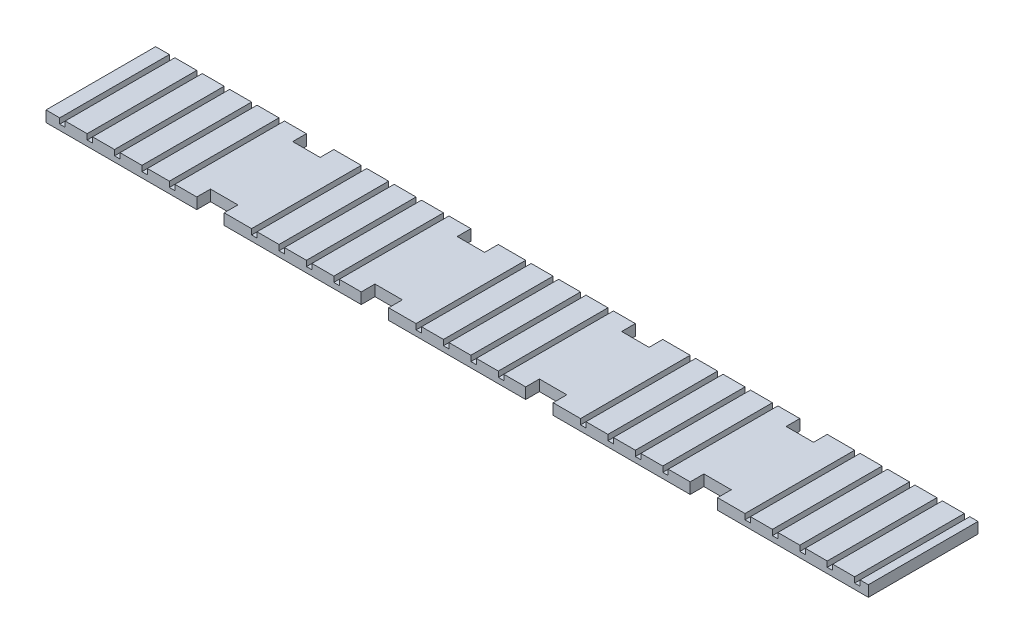
SolidWorks part; units mm, degrees
ref_plane "Front Plane" through (0, 0, 0) normal (0, 0, 1) x (1, 0, 0)
ref_plane "Top Plane" through (0, 0, 0) normal (0, 1, 0) x (1, 0, 0)
ref_plane "Right Plane" through (0, 0, 0) normal (1, 0, 0) x (0, 0, -1)
sketch "Sketch1" plane through (0, 0, 0) normal (0, 1, 0) x (1, 0, 0)
  line L0 (0, 20) -> (30, 20) construction
  line L1 (0, 0) -> (27.5, 0)
  line L2 (0, 0) -> (0, 20)
  line L3 (0, 20) -> (27.5, 20)
  line L4 (150, 0) -> (150, 20)
  line L5 (30, 20) -> (60, 20) construction
  line L6 (60, 20) -> (90, 20) construction
  line L7 (90, 20) -> (90.2101, 20) construction
  line L8 (90.2101, 20) -> (120, 20) construction
  line L10 (32.5, 20) -> (32.5, 17.5)
  line L11 (27.5, 20) -> (27.5, 17.5)
  line L12 (32.5, 17.5) -> (27.5, 17.5)
  line L13 (30, 20) -> (27.5, 17.5) construction
  line L14 (30, 20) -> (32.5, 17.5) construction
  line L15 (62.5, 20) -> (87.5, 20)
  line L16 (57.5, 20) -> (57.5, 17.5)
  line L17 (57.5, 17.5) -> (62.5, 17.5)
  line L18 (62.5, 17.5) -> (62.5, 20)
  line L20 (87.5, 20) -> (87.5, 17.5)
  line L21 (87.5, 17.5) -> (92.5, 17.5)
  line L22 (92.5, 17.5) -> (92.5, 20)
  line L23 (122.5, 20) -> (150, 20)
  line L24 (117.5, 20) -> (117.5, 17.5)
  line L25 (117.5, 17.5) -> (122.5, 17.5)
  line L26 (122.5, 17.5) -> (122.5, 20)
  line L27 (32.5, 20) -> (57.5, 20)
  line L28 (90, 20) -> (90.2101, 20)
  line L29 (92.5, 20) -> (117.5, 20)
  line L30 (27.5, 0) -> (27.5, 2.5)
  line L31 (27.5, 2.5) -> (32.5, 2.5)
  line L32 (32.5, 2.5) -> (32.5, 0)
  line L33 (57.5, 0) -> (57.5, 2.5)
  line L34 (57.5, 2.5) -> (62.5, 2.5)
  line L35 (62.5, 2.5) -> (62.5, 0)
  line L36 (87.5, 0) -> (87.5, 2.5)
  line L37 (87.5, 2.5) -> (92.5, 2.5)
  line L38 (92.5, 2.5) -> (92.5, 0)
  line L39 (117.5, 0) -> (117.5, 2.5)
  line L40 (117.5, 2.5) -> (122.5, 2.5)
  line L41 (122.5, 2.5) -> (122.5, 0)
  line L42 (32.5, 0) -> (57.5, 0)
  line L43 (62.5, 0) -> (87.5, 0)
  line L44 (92.5, 0) -> (117.5, 0)
  line L45 (122.5, 0) -> (150, 0)
  dimension "D1" = 27.5
  dimension "D2" = 32.5
  dimension "D3" = 57.5
  dimension "D4" = 17.5
  dimension "D7" = 90.2101
extrude "Boss-Extrude1" add sketch "Sketch1" along normal blind 2 contours L41 L45 L4 L23 L26 L25 L24 L29 L22 L21 L20 L15 L18 L17 L16 L27 L10 L12 L11 L3 L2 L1 L30 L31 L32 L42 L33 L34 L35 L43 L36 L37 L38 L44 L39 L40
sketch "Sketch2" plane through (0, 2, 0) normal (0, 1, 0) x (1, 0, 0)
  line L0 (0, 0) -> (27.5, 0) construction
  line L1 (2.5, 0) -> (3.5, 0)
  line L2 (2.5, 0) -> (2.5, 20)
  line L3 (2.5, 20) -> (3.5, 20)
  line L4 (3.5, 0) -> (3.5, 20)
  line L5 (0, 20) -> (27.5, 20) construction
  line L6 (0, 0) -> (0, 20) construction
  line L7 (7.5, 0) -> (7.5, 20)
  line L8 (7.5, 0) -> (8.5, 0)
  line L9 (8.5, 0) -> (8.5, 20)
  line L10 (7.5, 20) -> (8.5, 20)
  line L11 (12.5, 0) -> (12.5, 20)
  line L12 (12.5, 0) -> (13.5, 0)
  line L13 (13.5, 0) -> (13.5, 20)
  line L14 (12.5, 20) -> (13.5, 20)
  line L15 (17.5, 0) -> (17.5, 20)
  line L16 (17.5, 0) -> (18.5, 0)
  line L17 (18.5, 0) -> (18.5, 20)
  line L18 (17.5, 20) -> (18.5, 20)
  line L19 (22.5, 0) -> (22.5, 20)
  line L20 (22.5, 0) -> (23.5, 0)
  line L21 (23.5, 0) -> (23.5, 20)
  line L22 (22.5, 20) -> (23.5, 20)
  line L23 (27.5, 0) -> (27.5, 20) [skipped]
  line L24 (27.5, 0) -> (28.5, 0) [skipped]
  line L25 (28.5, 0) -> (28.5, 20) [skipped]
  line L26 (27.5, 20) -> (28.5, 20) [skipped]
  line L27 (32.5, 0) -> (32.5, 20) [skipped]
  line L28 (32.5, 0) -> (33.5, 0) [skipped]
  line L29 (33.5, 0) -> (33.5, 20) [skipped]
  line L30 (32.5, 20) -> (33.5, 20) [skipped]
  line L31 (37.5, 0) -> (37.5, 20)
  line L32 (37.5, 0) -> (38.5, 0)
  line L33 (38.5, 0) -> (38.5, 20)
  line L34 (37.5, 20) -> (38.5, 20)
  line L35 (42.5, 0) -> (42.5, 20)
  line L36 (42.5, 0) -> (43.5, 0)
  line L37 (43.5, 0) -> (43.5, 20)
  line L38 (42.5, 20) -> (43.5, 20)
  line L39 (47.5, 0) -> (47.5, 20)
  line L40 (47.5, 0) -> (48.5, 0)
  line L41 (48.5, 0) -> (48.5, 20)
  line L42 (47.5, 20) -> (48.5, 20)
  line L43 (52.5, 0) -> (52.5, 20)
  line L44 (52.5, 0) -> (53.5, 0)
  line L45 (53.5, 0) -> (53.5, 20)
  line L46 (52.5, 20) -> (53.5, 20)
  line L47 (57.5, 0) -> (57.5, 20) [skipped]
  line L48 (57.5, 0) -> (58.5, 0) [skipped]
  line L49 (58.5, 0) -> (58.5, 20) [skipped]
  line L50 (57.5, 20) -> (58.5, 20) [skipped]
  line L51 (62.5, 0) -> (62.5, 20) [skipped]
  line L52 (62.5, 0) -> (63.5, 0) [skipped]
  line L53 (63.5, 0) -> (63.5, 20) [skipped]
  line L54 (62.5, 20) -> (63.5, 20) [skipped]
  line L55 (67.5, 0) -> (67.5, 20)
  line L56 (67.5, 0) -> (68.5, 0)
  line L57 (68.5, 0) -> (68.5, 20)
  line L58 (67.5, 20) -> (68.5, 20)
  line L59 (72.5, 0) -> (72.5, 20)
  line L60 (72.5, 0) -> (73.5, 0)
  line L61 (73.5, 0) -> (73.5, 20)
  line L62 (72.5, 20) -> (73.5, 20)
  line L63 (77.5, 0) -> (77.5, 20)
  line L64 (77.5, 0) -> (78.5, 0)
  line L65 (78.5, 0) -> (78.5, 20)
  line L66 (77.5, 20) -> (78.5, 20)
  line L67 (82.5, 0) -> (82.5, 20)
  line L68 (82.5, 0) -> (83.5, 0)
  line L69 (83.5, 0) -> (83.5, 20)
  line L70 (82.5, 20) -> (83.5, 20)
  line L71 (87.5, 0) -> (87.5, 20) [skipped]
  line L72 (87.5, 0) -> (88.5, 0) [skipped]
  line L73 (88.5, 0) -> (88.5, 20) [skipped]
  line L74 (87.5, 20) -> (88.5, 20) [skipped]
  line L75 (92.5, 0) -> (92.5, 20) [skipped]
  line L76 (92.5, 0) -> (93.5, 0) [skipped]
  line L77 (93.5, 0) -> (93.5, 20) [skipped]
  line L78 (92.5, 20) -> (93.5, 20) [skipped]
  line L79 (97.5, 0) -> (97.5, 20)
  line L80 (97.5, 0) -> (98.5, 0)
  line L81 (98.5, 0) -> (98.5, 20)
  line L82 (97.5, 20) -> (98.5, 20)
  line L83 (102.5, 0) -> (102.5, 20)
  line L84 (102.5, 0) -> (103.5, 0)
  line L85 (103.5, 0) -> (103.5, 20)
  line L86 (102.5, 20) -> (103.5, 20)
  line L87 (107.5, 0) -> (107.5, 20)
  line L88 (107.5, 0) -> (108.5, 0)
  line L89 (108.5, 0) -> (108.5, 20)
  line L90 (107.5, 20) -> (108.5, 20)
  line L91 (112.5, 0) -> (112.5, 20)
  line L92 (112.5, 0) -> (113.5, 0)
  line L93 (113.5, 0) -> (113.5, 20)
  line L94 (112.5, 20) -> (113.5, 20)
  line L95 (117.5, 0) -> (117.5, 20) [skipped]
  line L96 (117.5, 0) -> (118.5, 0) [skipped]
  line L97 (118.5, 0) -> (118.5, 20) [skipped]
  line L98 (117.5, 20) -> (118.5, 20) [skipped]
  line L99 (122.5, 0) -> (122.5, 20) [skipped]
  line L100 (122.5, 0) -> (123.5, 0) [skipped]
  line L101 (123.5, 0) -> (123.5, 20) [skipped]
  line L102 (122.5, 20) -> (123.5, 20) [skipped]
  line L103 (127.5, 0) -> (127.5, 20)
  line L104 (127.5, 0) -> (128.5, 0)
  line L105 (128.5, 0) -> (128.5, 20)
  line L106 (127.5, 20) -> (128.5, 20)
  line L107 (132.5, 0) -> (132.5, 20)
  line L108 (132.5, 0) -> (133.5, 0)
  line L109 (133.5, 0) -> (133.5, 20)
  line L110 (132.5, 20) -> (133.5, 20)
  line L111 (137.5, 0) -> (137.5, 20)
  line L112 (137.5, 0) -> (138.5, 0)
  line L113 (138.5, 0) -> (138.5, 20)
  line L114 (137.5, 20) -> (138.5, 20)
  line L115 (142.5, 0) -> (142.5, 20)
  line L116 (142.5, 0) -> (143.5, 0)
  line L117 (143.5, 0) -> (143.5, 20)
  line L118 (142.5, 20) -> (143.5, 20)
  line L119 (147.5, 0) -> (147.5, 20)
  line L120 (147.5, 0) -> (148.5, 0)
  line L121 (148.5, 0) -> (148.5, 20)
  line L122 (147.5, 20) -> (148.5, 20)
  line L123 (150, 0) -> (150, 20) construction
  line L124 (122.5, 0) -> (150, 0) construction
  dimension "D1" = 1
  dimension "D2" = 2.5
  dimension "D4" = 1.5
  dimension "D3" = 30
extrude "Cut-Extrude1" cut sketch "Sketch2" against normal blind 1
